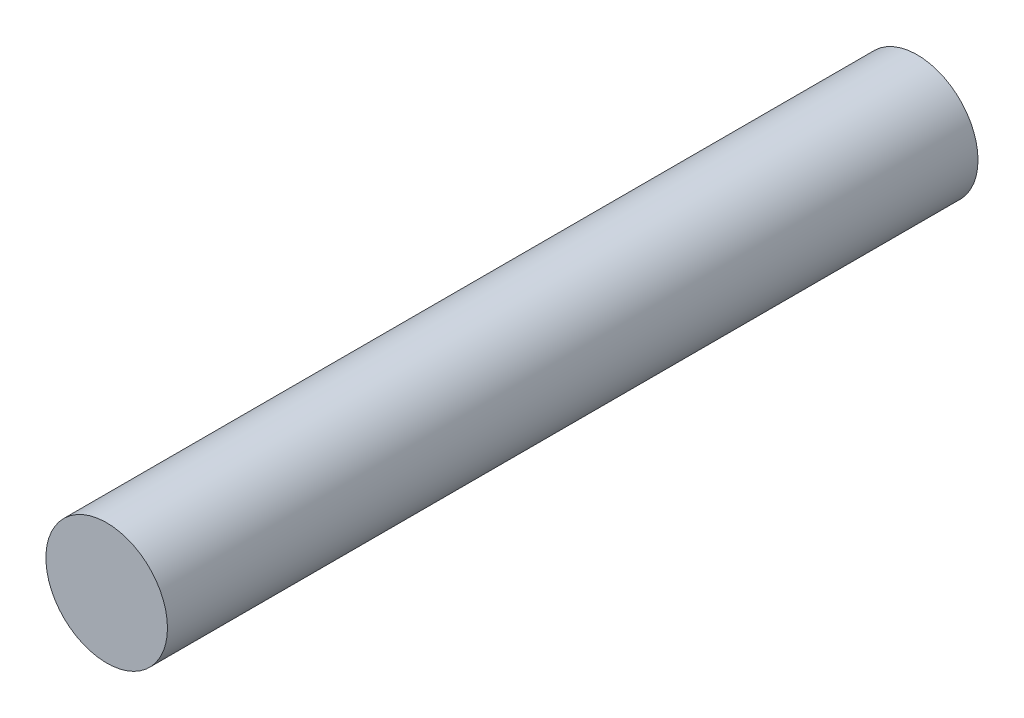
SolidWorks part; units mm, degrees
material "AISI 304"
ref_plane "Front" through (0, 0, 0) normal (0, 0, 1) x (1, 0, 0)
ref_plane "Top" through (0, 0, 0) normal (0, 1, 0) x (1, 0, 0)
ref_plane "Right" through (0, 0, 0) normal (1, 0, 0) x (0, 0, -1)
sketch "Sketch1" plane through (0, 0, 0) normal (0, 0, 1) x (1, 0, 0)
  circle A0 centre (0, 0) radius 1.5
  dimension "D1" = 3
extrude "Boss-Extrude1" add sketch "Sketch1" along normal blind 20
